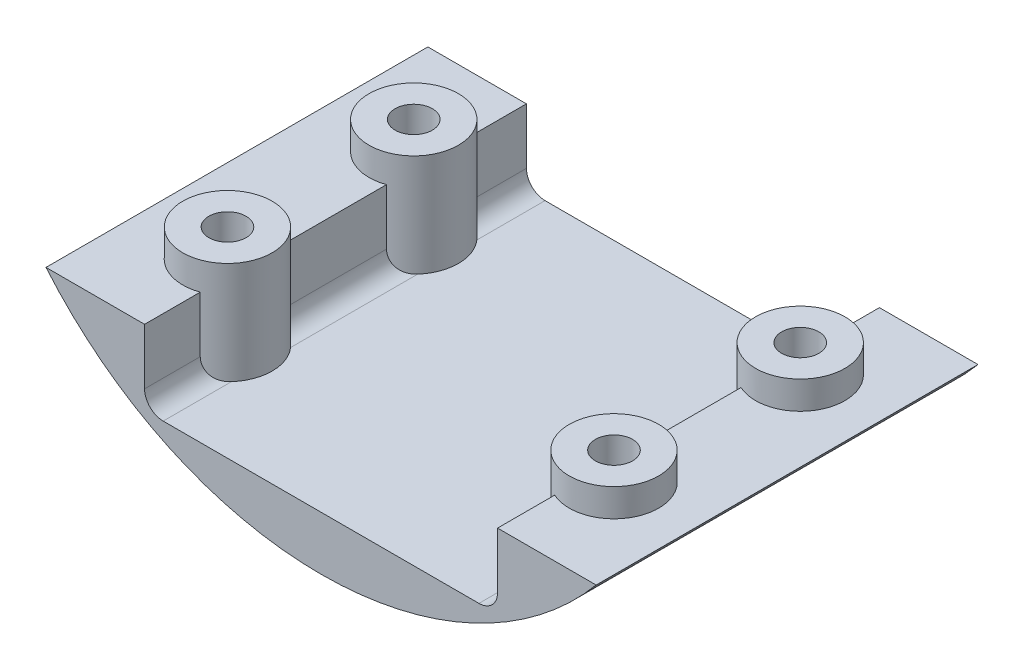
SolidWorks part; units mm, degrees
ref_plane "Front Plane" through (0, 0, 0) normal (0, 0, 1) x (1, 0, 0)
ref_plane "Top Plane" through (0, 0, 0) normal (0, 1, 0) x (1, 0, 0)
ref_plane "Right Plane" through (0, 0, 0) normal (1, 0, 0) x (0, 0, -1)
sketch "Sketch2" plane through (0, 0, 0) normal (0, 0, 1) x (1, 0, 0)
  line L0 (-29.5334, -24.7767) -> (29.5334, -24.7767)
  line L2 (29.7, -24.5767) -> (18.95, -24.5767) construction
  arc A0 (-29.5334, -24.7767) -> (29.5334, -24.7767) centre (0, 0) ccw
  arc A2 (29.7, 24.5767) -> (-29.7, -24.5767) centre (0, 0) ccw construction
  dimension "D1" = 0.2
extrude "Boss-Extrude1" add sketch "Sketch2" against normal up to surface (41 mm away)
sketch "Sketch3" plane through (0, -24.7767, 0) normal (0, 1, 0) x (1, 0, 0)
  circle A0 centre (20.95, 10.5) radius 4.8
  circle A1 centre (20.95, 10.5) radius 5 construction
  circle A2 centre (20.95, 30.5) radius 4.8
  circle A3 centre (-20.55, 30.5) radius 4.8
  circle A4 centre (-20.55, 10.5) radius 4.8
  circle A5 centre (20.95, 30.5) radius 2
  circle A6 centre (20.95, 10.5) radius 2
  circle A7 centre (-20.55, 10.5) radius 2
  circle A8 centre (-20.55, 30.5) radius 2
  dimension "D1" = 0.2
  dimension "D2" = 4
extrude "Boss-Extrude2" add sketch "Sketch3" along normal blind 3
sketch "Sketch4" plane through (0, -24.7767, 0) normal (0, 1, 0) x (1, 0, 0)
  line L0 (-29.5334, 41) -> (29.5334, 41) construction
  line L5 (-18.95, 0) -> (18.95, 0)
  line L6 (-18.95, 0) -> (-18.95, 41)
  line L7 (-18.95, 41) -> (18.95, 41)
  line L8 (18.95, 0) -> (18.95, 41)
  line L9 (-18.95, 0) -> (18.95, 41) construction
  line L10 (-18.95, 41) -> (18.95, 0) construction
  line L13 (29.5334, 0) -> (-29.5334, 0) construction
  point P0 (0, 20.5)
  point P9 (10.8723, 3.1)
  point P10 (0, 0)
  circle M1 centre (-20.55, 10.5) radius 4.8
  circle M2 centre (-20.55, 30.5) radius 4.8
  circle M3 centre (20.95, 30.5) radius 4.8
  circle M4 centre (20.95, 10.5) radius 4.8
  line M5 (29.5334, 41) -> (-29.5334, 41)
  line M7 (-29.5334, 0) -> (29.5334, 0)
  dimension "D1" = 37.9
extrude "Cut-Extrude1" cut sketch "Sketch4" against normal blind 8 contours L8 L6 M7 M4 M3 M5 M2 M1
fillet "Fillet1" radius 2 6 edges at (18.95, -32.7767, -37.9317) (18.95, -32.7767, -20.5) (-18.95, -32.7767, -38.0127) (-18.95, -32.7767, -20.5) (-18.95, -32.7767, -2.9873) (18.95, -32.7767, -3.0683)
